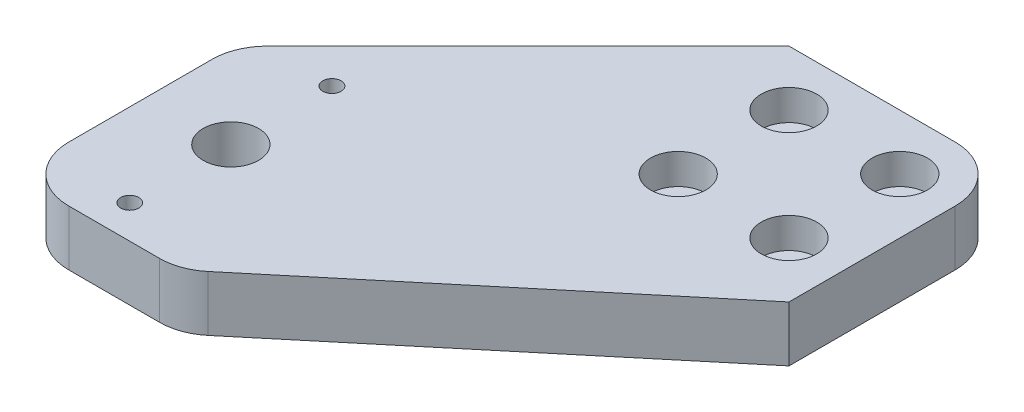
SolidWorks part; units mm, degrees
material "ALUMINIUM,  6082-T6"
ref_plane "Front Plane" through (0, 0, 0) normal (0, 0, 1) x (1, 0, 0)
ref_plane "Top Plane" through (0, 0, 0) normal (0, 1, 0) x (1, 0, 0)
ref_plane "Right Plane" through (0, 0, 0) normal (1, 0, 0) x (0, 0, -1)
sketch "Sketch1" plane through (0, 0, 0) normal (0, 1, 0) x (1, 0, 0)
  line L0 (20, 20) -> (-20, -20) construction
  line L1 (-20, 20) -> (20, 20)
  line L2 (-20, 20) -> (-20, -20) construction
  line L3 (-20, -20) -> (20, -20) construction
  line L4 (20, 20) -> (20, -20)
  line L5 (-20, 20) -> (-70, -30)
  line L6 (-70, -30) -> (-70, -70)
  line L8 (-70, -70) -> (-40, -70)
  line L9 (-40, -70) -> (20, -20)
  dimension "D1" = 40
  dimension "D2" = 40
  dimension "D3" = 50
  dimension "D4" = 50
  dimension "D5" = 40
  dimension "D6" = 30
  dimension "D7" = 50
extrude "Boss-Extrude1" add sketch "Sketch1" along normal mid plane 10
hole_wizard "CBORE for M5 Hex Socket Head Cap Screw2" positions "Sketch2" profile "Sketch3" counterbore size "M5" standard "ISO" end condition through all
sketch "Sketch2" plane through (0, 5, 0) normal (0, 1, 0) x (1, 0, 0)
  line L0 (-10, 10) -> (-10, -10) construction
  line L1 (-10, -10) -> (10, -10) construction
  line L2 (10, -10) -> (10, 10) construction
  line L3 (10, 10) -> (-10, 10) construction
  line L4 (-10, 10) -> (10, -10) construction
  point P0 (-10, 10)
  point P2 (10, 10)
  point P4 (10, -10)
  point P6 (-10, -10)
  dimension "D1" = 20
sketch "Sketch3" plane through (-10, 5, -10) normal (1, 0, 0) x (0, 0, 1)
  line L0 (0, 0) -> (0, 10)
  line L1 (0, 10) -> (2.75, 10)
  line L3 (2.75, 10) -> (2.75, 5.5)
  line L4 (2.75, 5.5) -> (5, 5.5)
  line L5 (5, 5.5) -> (5, 0)
  line L7 (5, 0) -> (0, 0)
  line L11 (0, -6.35) -> (0, 107.95) construction
  dimension "Thru Hole Dia." = 5.5
  dimension "Thru Hole Depth" = 10
  dimension "C'Bore Dia." = 10
  dimension "C'Bore Depth" = 5.5
hole_wizard "M4 Tapped Hole1" positions "Sketch4" profile "Sketch5" tap size "M4" standard "ISO" end condition through all
sketch "Sketch4" plane through (0, 5, 0) normal (0, 1, 0) x (1, 0, 0)
  line L0 (-55, -27.5) -> (-55, -64) construction
  line L4 (-70, -30) -> (-70, -70) construction
  line L5 (-70, -70) -> (-40, -70) construction
  point P0 (-55, -27.5)
  point P2 (-55, -64)
  dimension "D1" = 36.5
  dimension "D2" = 15
  dimension "D3" = 6
sketch "Sketch5" plane through (-55, 5, 27.5) normal (1, 0, 0) x (0, 0, 1)
  line L0 (0, 0) -> (0, 10)
  line L1 (0, 10) -> (1.65, 10)
  line L2 (1.65, 10) -> (1.65, 0)
  line L5 (1.65, 0) -> (0, 0)
  line L11 (0, -6.35) -> (0, 107.95) construction
  dimension "Thru Tap Drill Dia." = 3.3
  dimension "Thru Tap Drill Depth" = 10
cosmetic thread "Hole Thread1" parameters "D2"=4
cosmetic thread "Hole Thread2" parameters "D2"=4
sketch "Sketch8" plane through (0, 5, 0) normal (0, 1, 0) x (1, 0, 0)
  line L0 (-55, -27.5) -> (-55, -64) construction
  circle A0 centre (-55, -45.75) radius 5
  dimension "D1" = 10
extrude "Cut-Extrude3" cut sketch "Sketch8" against normal through all
fillet "Fillet1" radius 10 4 edges at (20, 0, -20) (-40, 0, 70) (-70, 0, 70) (-70, 0, 30)
sketch "Sketch7" [suppressed] plane through (0, 10, 0) normal (0, 1, 0) x (1, 0, 0)
  line L0 (-37.2187, -67.6822) -> (20, -20) construction
  line L1 (20, -20) -> (20, 10) construction
  line L2 (10, 20) -> (-20, 20) construction
  line L3 (-20, 20) -> (-67.0711, -27.0711) construction
  line L4 (16.4018, -22.9985) -> (20, -20)
  line L5 (20, -20) -> (20, -15.3163)
  line L6 (-15.8579, 20) -> (-20, 20)
  line L7 (-20, 20) -> (-22.9289, 17.0711)
  arc A0 (-22.9289, 17.0711) -> (-15.8579, 20) centre (-15.8579, 10) cw
  arc A1 (20, -15.3163) -> (16.4018, -22.9985) centre (10, -15.3163) cw
  dimension "D1" = 10
extrude "Cut-Extrude2" [suppressed] cut sketch "Sketch7" against normal through all
chamfer "Chamfer1" [suppressed] distance 0.5 angle 45
